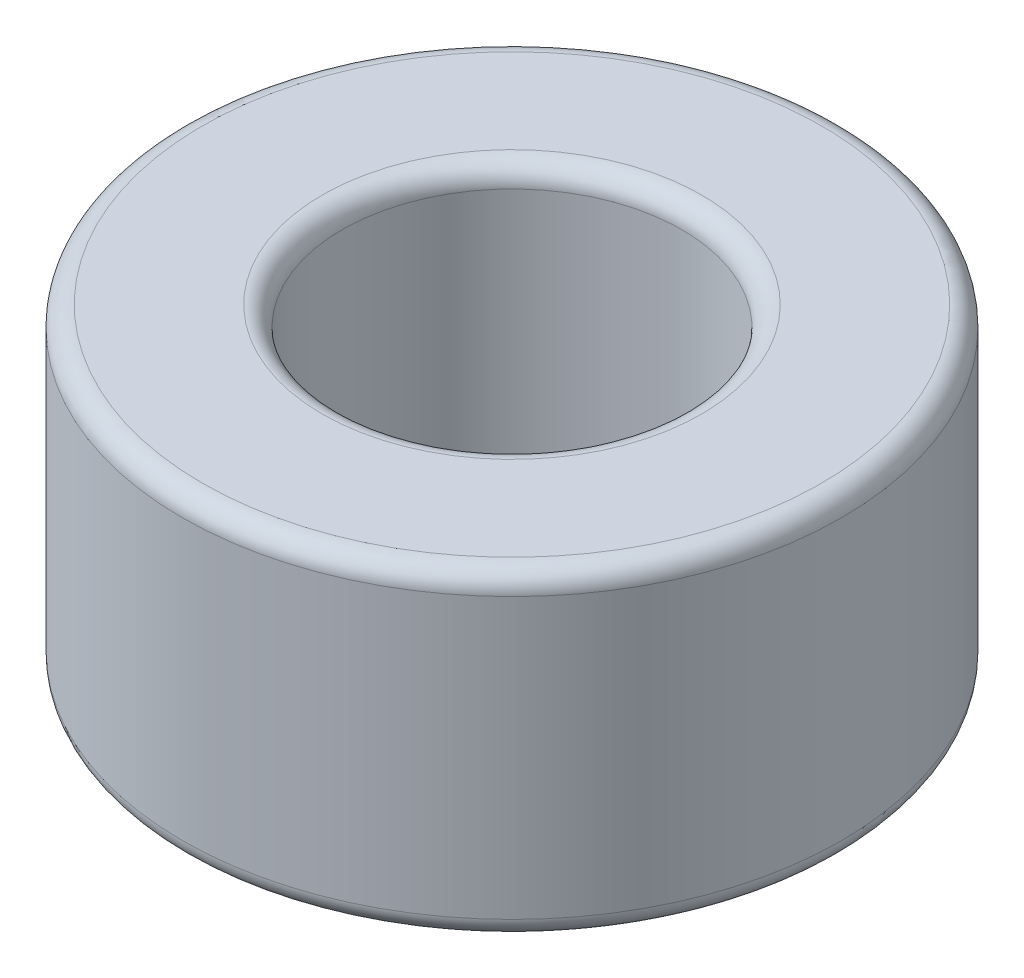
SolidWorks part; units mm, degrees
ref_plane "Front Plane" through (0, 0, 0) normal (0, 0, 1) x (1, 0, 0)
ref_plane "Top Plane" through (0, 0, 0) normal (0, 1, 0) x (1, 0, 0)
ref_plane "Right Plane" through (0, 0, 0) normal (1, 0, 0) x (0, 0, -1)
sketch "Sketch1" plane through (0, 0, 0) normal (0, 1, 0) x (1, 0, 0)
  circle A0 centre (0, 0) radius 8.25
  circle A1 centre (0, 0) radius 4.25
  dimension "D1" = 16.5
  dimension "D2" = 8.5
extrude "Boss-Extrude1" add sketch "Sketch1" along normal blind 8
fillet "Fillet1" radius 0.5 4 edges at (0, 0, 8.25) (0, 0, 4.25) (0, 8, 8.25) (0, 8, 4.25)
